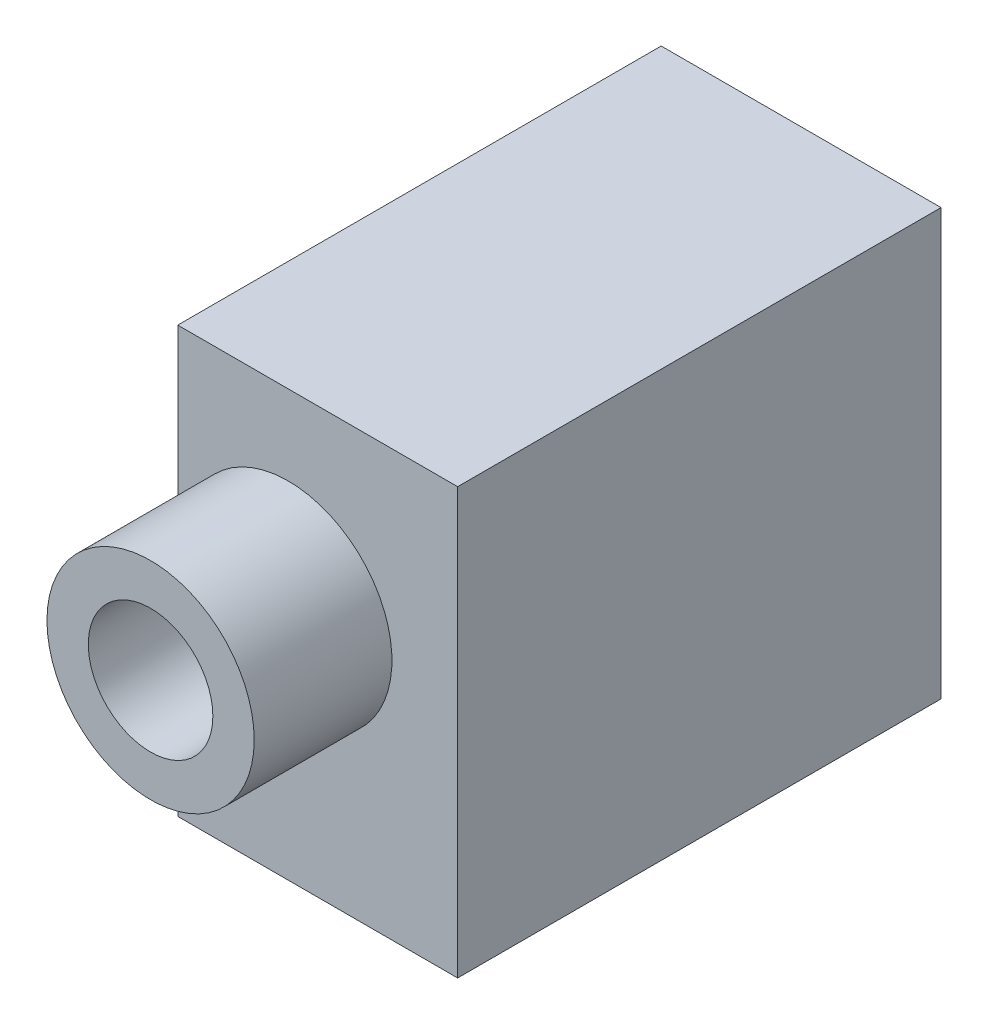
SolidWorks part; units mm, degrees
ref_plane "Front Plane" through (0, 0, 0) normal (0, 0, 1) x (1, 0, 0)
ref_plane "Top Plane" through (0, 0, 0) normal (0, 1, 0) x (1, 0, 0)
ref_plane "Right Plane" through (0, 0, 0) normal (1, 0, 0) x (0, 0, -1)
sketch "Sketch1" plane through (0, 0, 0) normal (0, 1, 0) x (1, 0, 0)
  line L1 (-3.2004, 0) -> (4.9022, 0)
  line L2 (-3.2004, 0) -> (-3.2004, 13.9954)
  line L3 (-3.2004, 13.9954) -> (4.9022, 13.9954)
  line L4 (4.9022, 0) -> (4.9022, 13.9954)
  dimension "D1" = 3.2004
  dimension "D2" = 4.9022
  dimension "D3" = 13.9954
extrude "Boss-Extrude1" add sketch "Sketch1" along normal blind 12.319
sketch "Sketch2" plane through (0, 0, 0) normal (0, 0, 1) x (1, 0, 0)
  line L0 (4.9022, 12.319) -> (4.9022, 0) construction
  circle A0 centre (0, 7.0104) radius 1.8034
  circle A1 centre (0, 7.0104) radius 3
  dimension "D3" = 3.6068
  dimension "D4" = 6
  dimension "D1" = 7.0104
  dimension "D2" = 4.9022
extrude "Boss-Extrude2" add sketch "Sketch2" along normal blind 3.9878
